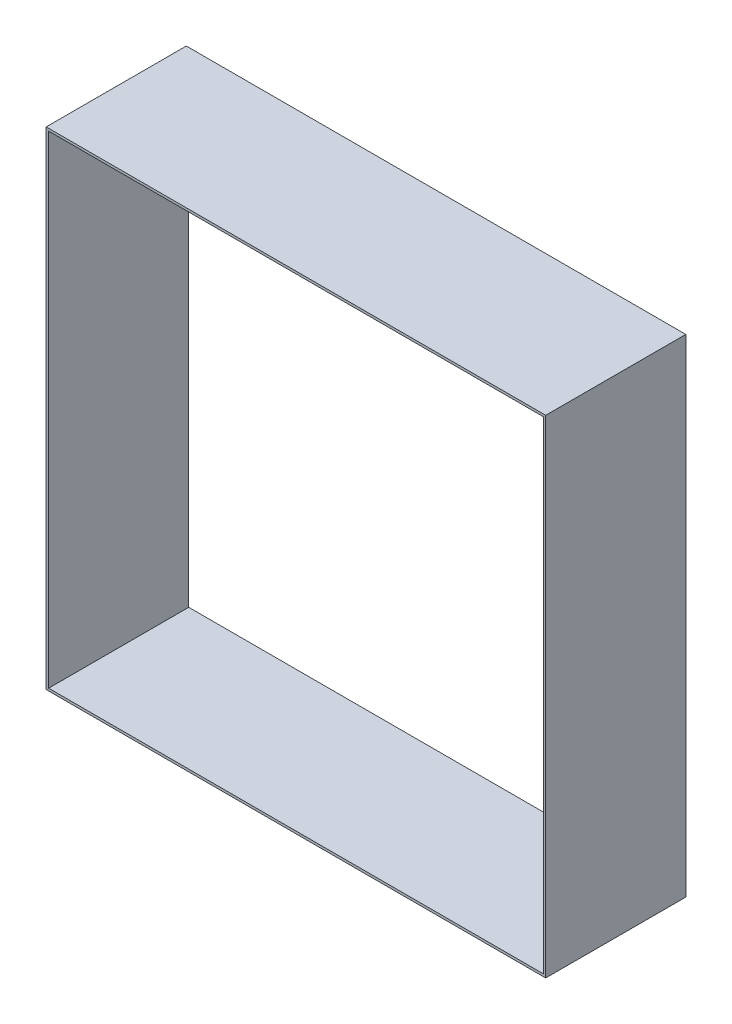
SolidWorks part; units mm, degrees
ref_plane "정면" through (0, 0, 0) normal (0, 0, 1) x (1, 0, 0)
ref_plane "윗면" through (0, 0, 0) normal (0, 1, 0) x (1, 0, 0)
ref_plane "우측면" through (0, 0, 0) normal (1, 0, 0) x (0, 0, -1)
sketch "스케치1" plane through (0, 0, 0) normal (0, 0, 1) x (1, 0, 0)
  line L0 (0.2, 0.2) -> (40.8, 0.2)
  line L1 (0, 0) -> (41, 0)
  line L2 (0, 0) -> (0, 40)
  line L3 (0, 40) -> (41, 40)
  line L4 (41, 0) -> (41, 40)
  line L5 (40.8, 0.2) -> (40.8, 39.8)
  line L6 (0.2, 39.8) -> (40.8, 39.8)
  line L7 (0.2, 0.2) -> (0.2, 39.8)
  dimension "D1" = 41
  dimension "D2" = 40
  dimension "D3" = 0.2
extrude "보스-돌출1" add sketch "스케치1" along normal blind 11.5
